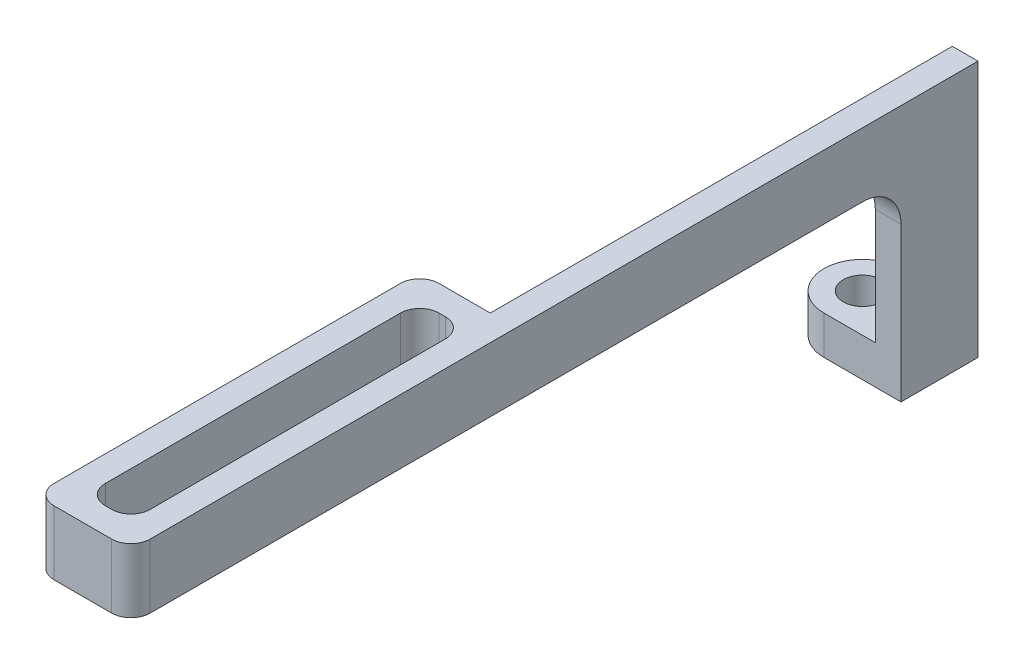
SolidWorks part; units mm, degrees
ref_plane "前视基准面" through (0, 0, 0) normal (0, 0, 1) x (1, 0, 0)
ref_plane "上视基准面" through (0, 0, 0) normal (0, 1, 0) x (1, 0, 0)
ref_plane "右视基准面" through (0, 0, 0) normal (1, 0, 0) x (0, 0, -1)
other "Configuration Table"
sketch "草图1" plane through (0, 0, 0) normal (0, 1, 0) x (1, 0, 0)
  line L0 (0, 3) -> (6, 3)
  line L1 (6, 3) -> (6, -3)
  line L2 (6, -3) -> (0, -3)
  circle A0 centre (0, 0) radius 1.5
  circle A1 centre (0, 0) radius 3
  dimension "D1" = 6
  dimension "D2" = 6
  dimension "D3" = 3
extrude "凸台-拉伸1" add sketch "草图1" along normal blind 3 contours A1 L2 L1 L0 | A1 A0
sketch "草图2" plane through (0, 0, 0) normal (0, 1, 0) x (1, 0, 0)
  line L0 (4, 3) -> (6, 3)
  line L1 (0, 3) -> (6, 3) construction
  line L2 (6, 3) -> (6, -3)
  line L3 (6, -3) -> (4, -3)
  line L4 (6, -3) -> (0, -3) construction
  line L5 (4, -3) -> (4, 3)
  dimension "D1" = 2
extrude "凸台-拉伸2" add sketch "草图2" along normal blind 15
ref_plane "基准面1" through (0, 15, 0) normal (0, 1, 0) x (1, 0, 0)
sketch "草图3" plane through (0, 15, 0) normal (0, 1, 0) x (1, 0, 0)
  line L0 (6, 3) -> (6, -63)
  line L1 (6, 3) -> (4, 3)
  line L2 (4, 3) -> (4, -33)
  line L3 (4, -63) -> (6, -63)
  line L4 (4, -33) -> (-1.5, -33)
  line L5 (-1.5, -33) -> (-1.5, -63)
  line L6 (-1.5, -63) -> (0.0941, -63)
  line L7 (0.0941, -63) -> (4, -63)
  line L8 (4, -35) -> (0.5, -35)
  line L9 (0.5, -35) -> (0.5, -61)
  line L10 (0.5, -61) -> (4, -61)
  line L11 (4, -35) -> (4, -61)
  dimension "D1" = 66
  dimension "D2" = 3.5
  dimension "D3" = 2
  dimension "D4" = 2
  dimension "D5" = 2
  dimension "D6" = 30
extrude "凸台-拉伸3" add sketch "草图3" along normal blind 5
fillet "圆角1" radius 3 1 edges at (5, 15, 3)
fillet "圆角2" radius 1.5 7 edges at (-1.5, 17.5, 33) (-1.5, 17.5, 63) (6, 17.5, 63) (4, 17.5, 61) (0.5, 17.5, 61) (4, 17.5, 35) (0.5, 17.5, 35)
